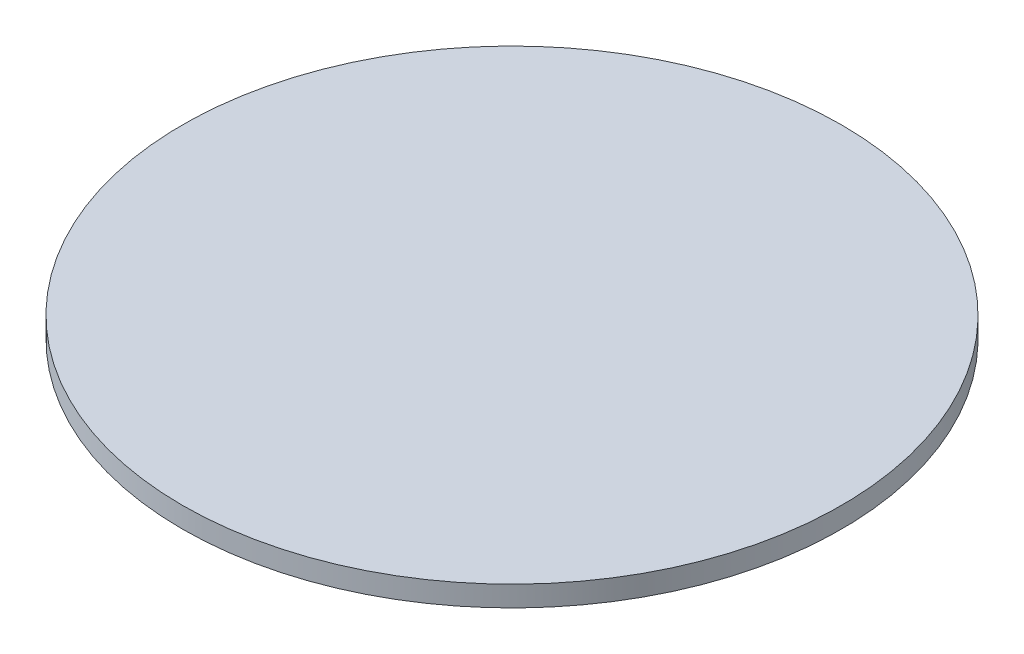
SolidWorks part; units mm, degrees
ref_plane "Front Plane" through (0, 0, 0) normal (0, 0, 1) x (1, 0, 0)
ref_plane "Top Plane" through (0, 0, 0) normal (0, 1, 0) x (1, 0, 0)
ref_plane "Right Plane" through (0, 0, 0) normal (1, 0, 0) x (0, 0, -1)
sketch "Sketch1" plane through (0, 0, 0) normal (0, 1, 0) x (1, 0, 0)
  circle A0 centre (0, 0) radius 50.8
  dimension "D1" = 101.6
extrude "Extrude1" add sketch "Sketch1" along normal blind 3.175
